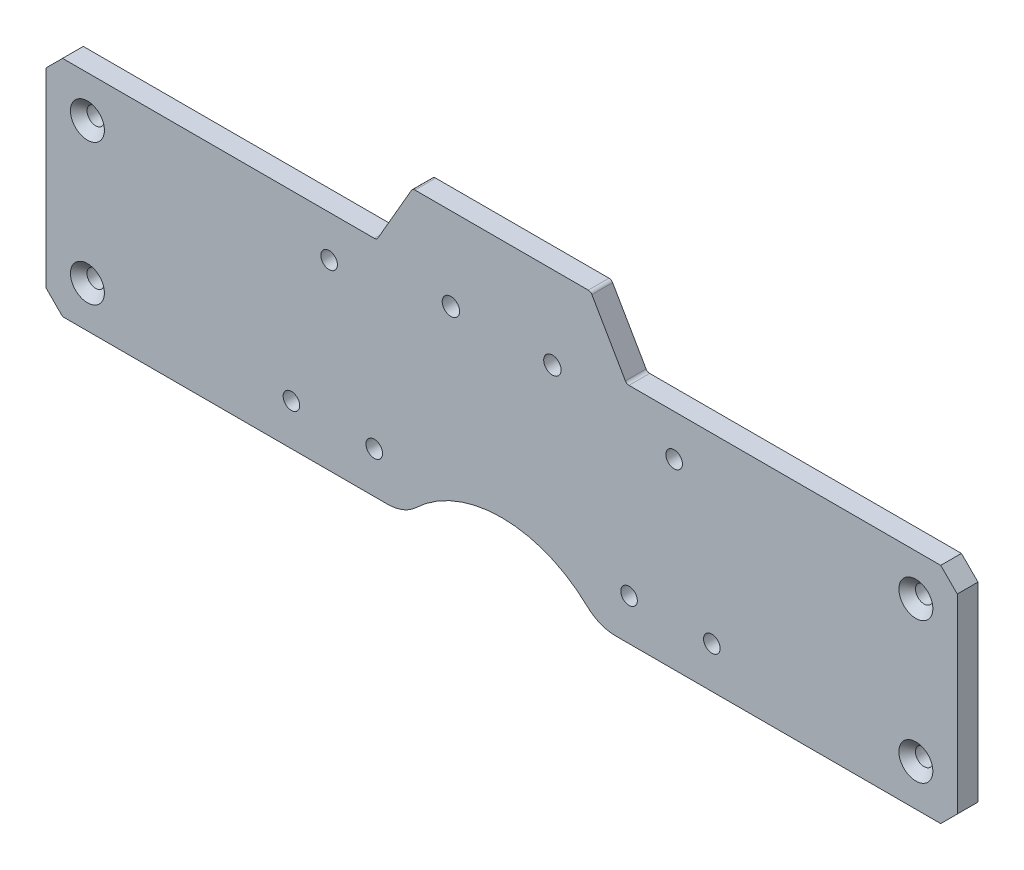
SolidWorks part; units mm, degrees
ref_plane "前视基准面" through (0, 0, 0) normal (0, 0, 1) x (1, 0, 0)
ref_plane "上视基准面" through (0, 0, 0) normal (0, 1, 0) x (1, 0, 0)
ref_plane "右视基准面" through (0, 0, 0) normal (1, 0, 0) x (0, 0, -1)
sketch "草图1" plane through (0, 0, 0) normal (0, 0, 1) x (1, 0, 0)
  line L0 (12.25, 22) -> (-12.25, 22) construction
  line L1 (110, -27) -> (-110, -27)
  line L2 (110, -27) -> (110, 27)
  line L3 (110, 27) -> (-110, 27)
  line L4 (-110, -27) -> (-110, 27)
  line L5 (110, -27) -> (-110, 27) construction
  line L6 (110, 27) -> (-110, -27) construction
  line L7 (100, -17) -> (-100, -17) construction
  line L8 (100, -17) -> (100, 17) construction
  line L9 (100, 17) -> (-100, 17) construction
  line L10 (-100, -17) -> (-100, 17) construction
  line L11 (100, -17) -> (-100, 17) construction
  line L12 (100, 17) -> (-100, -17) construction
  circle A0 centre (-100, 17) radius 2.1
  circle A1 centre (-100, -17) radius 2.1
  circle A2 centre (100, 17) radius 2.1
  circle A3 centre (100, -17) radius 2.1
  circle A10 centre (-12.25, 22) radius 2.1
  circle A11 centre (12.25, 22) radius 2.1
  point P0 (0, 0)
  point P8 (0, 0)
  point P18 (0, 0)
  point P21 (0, 22)
  dimension "D1" = 10
  dimension "D2" = 10
  dimension "D3" = 4.2
  dimension "D4" = 54
  dimension "D5" = 4.2
  dimension "D6" = 24.5
  dimension "D7" = 22
  dimension "D8" = 200
extrude "凸台-拉伸1" add sketch "草图1" along normal mid plane 5
chamfer "倒角1" distance 4 angle 45 4 edges at (-110, 27, 0) (-110, -27, 0) (110, -27, 0) (110, 27, 0)
chamfer "倒角2" distance 2 angle 45 6 edges at (-10.15, 22, -2.5) (14.35, 22, -2.5) (102.1, -17, 2.5) (102.1, 17, 2.5) (-97.9, 17, 2.5) (-97.9, -17, 2.5)
sketch "草图3" plane through (0, 0, 2.5) normal (0, 0, 1) x (1, 0, 0)
  line L0 (0, -156) -> (0, 0) construction
  line L1 (-91.763, -180.5878) -> (91.763, -131.4122) construction
  line L2 (91.763, -131.4122) -> (52.9401, 13.4767) construction
  line L3 (106, 27) -> (-106, 27) construction
  line L4 (50.7535, -17) -> (41.6433, 17) construction
  line L5 (-106, -27) -> (106, -27) construction
  circle A0 centre (50.7535, -17) radius 2
  circle A1 centre (41.6433, 17) radius 2
  circle A2 centre (30.7535, -17) radius 2
  circle A3 centre (-41.6433, 17) radius 2
  circle A4 centre (-50.7535, -17) radius 2
  circle A5 centre (-30.7535, -17) radius 2
  point P6 (0, -156)
  dimension "D5" = 4
  dimension "D6" = 10
  dimension "D7" = 10
  dimension "D8" = 10
  dimension "D9" = 20
  dimension "D1" = 190
  dimension "D2" = 183
  dimension "D3" = 150
  dimension "D4" = 15
extrude "切除-拉伸1" cut sketch "草图3" against normal through all
sketch "草图4" plane through (0, 0, 2.5) normal (0, 0, 1) x (1, 0, 0)
  line L0 (106, 27) -> (-106, 27) construction
  circle A0 centre (0, -46) radius 30
  dimension "D1" = 73
  dimension "D2" = 60
extrude "切除-拉伸2" cut sketch "草图4" against normal through all
fillet "圆角1" radius 10 2 edges at (23.2164, -27, 0) (-23.2164, -27, 0)
sketch "草图5" plane through (0, 0, -2.5) normal (0, 0, -1) x (-1, 0, 0)
  line L0 (-21.5, 42) -> (21.5, 42)
  line L1 (-106, 27) -> (106, 27) construction
  line L2 (-21.5, 42) -> (-30.1603, 27)
  line L3 (21.5, 42) -> (30.1603, 27)
  line L4 (30.1603, 27) -> (-30.1603, 27)
  point P2 (0, 42)
  dimension "D1" = 15
  dimension "D2" = 43
  dimension "D3" = 120
extrude "凸台-拉伸2" add sketch "草图5" against normal up to surface (5 mm away) up to face at (0, -7.9645, 2.5)
fillet "圆角2" radius 1 4 edges at (21.5, 42, 0) (30.1603, 27, 0) (-21.5, 42, 0) (-30.1603, 27, 0)
